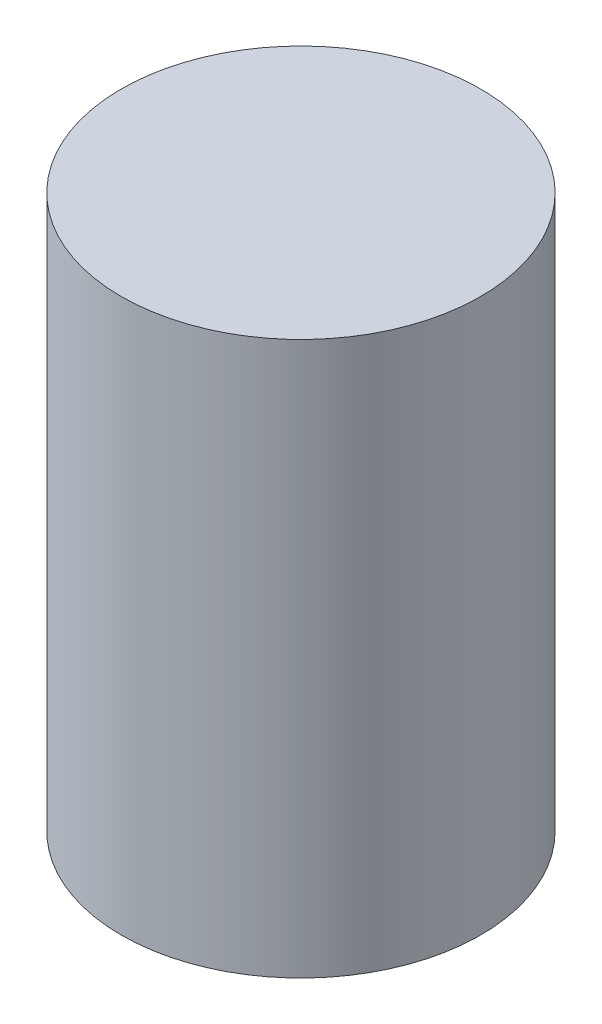
SolidWorks part; units mm, degrees
ref_plane "Front Plane" through (0, 0, 0) normal (0, 0, 1) x (1, 0, 0)
ref_plane "Top Plane" through (0, 0, 0) normal (0, 1, 0) x (1, 0, 0)
ref_plane "Right Plane" through (0, 0, 0) normal (1, 0, 0) x (0, 0, -1)
sketch "Sketch1" plane through (0, 0, 0) normal (0, 1, 0) x (1, 0, 0)
  circle A0 centre (0, 0) radius 2.6
  dimension "D1" = 5.2
extrude "Boss-Extrude1" add sketch "Sketch1" along normal blind 8
